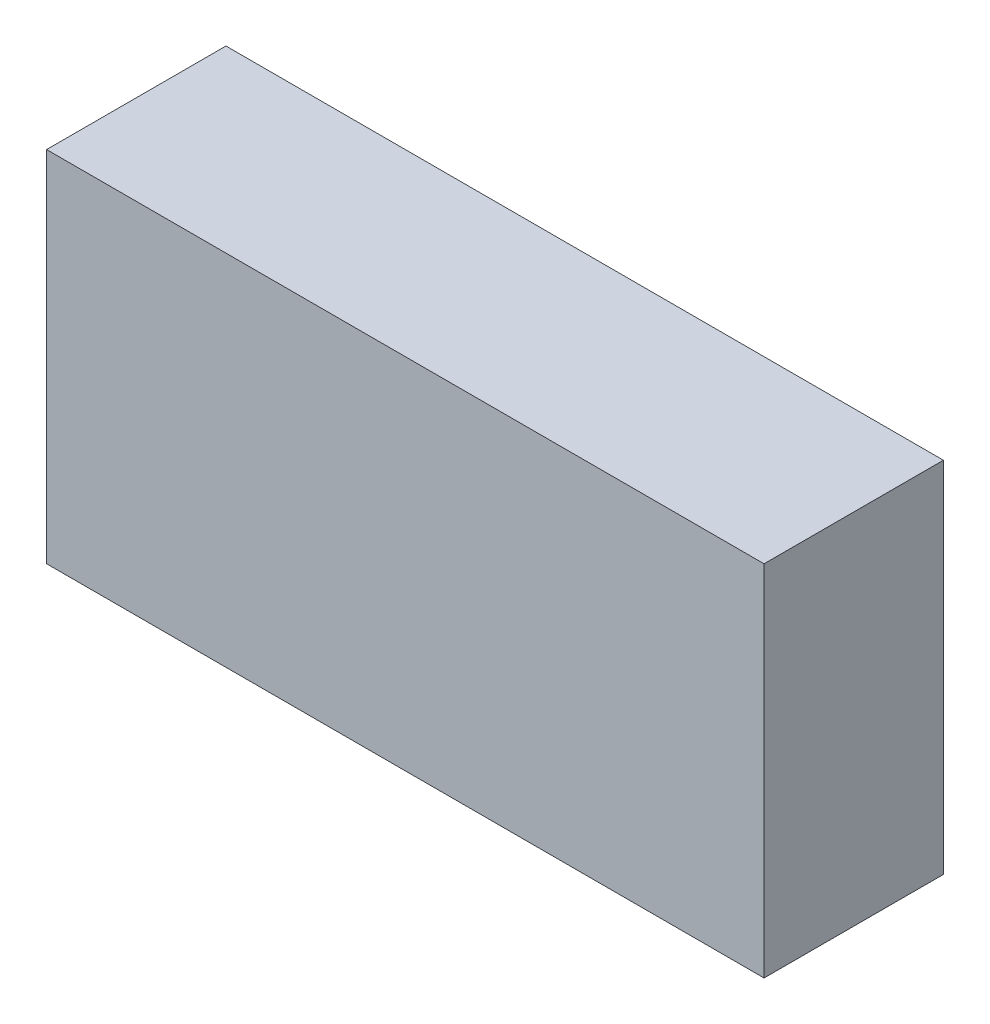
SolidWorks part; units mm, degrees
ref_plane "Front Plane" through (0, 0, 0) normal (0, 0, 1) x (1, 0, 0)
ref_plane "Top Plane" through (0, 0, 0) normal (0, 1, 0) x (1, 0, 0)
ref_plane "Right Plane" through (0, 0, 0) normal (1, 0, 0) x (0, 0, -1)
sketch "Sketch1" plane through (0, 0, 0) normal (0, 0, 1) x (1, 0, 0)
  line L0 (-20, -10) -> (20, -10)
  line L1 (20, -10) -> (20, 10)
  line L2 (20, 10) -> (-20, 10)
  line L3 (-20, 10) -> (-20, -10)
  dimension "D1" = 40
  dimension "D2" = 20
extrude "Boss-Extrude1" add sketch "Sketch1" along normal blind 10
